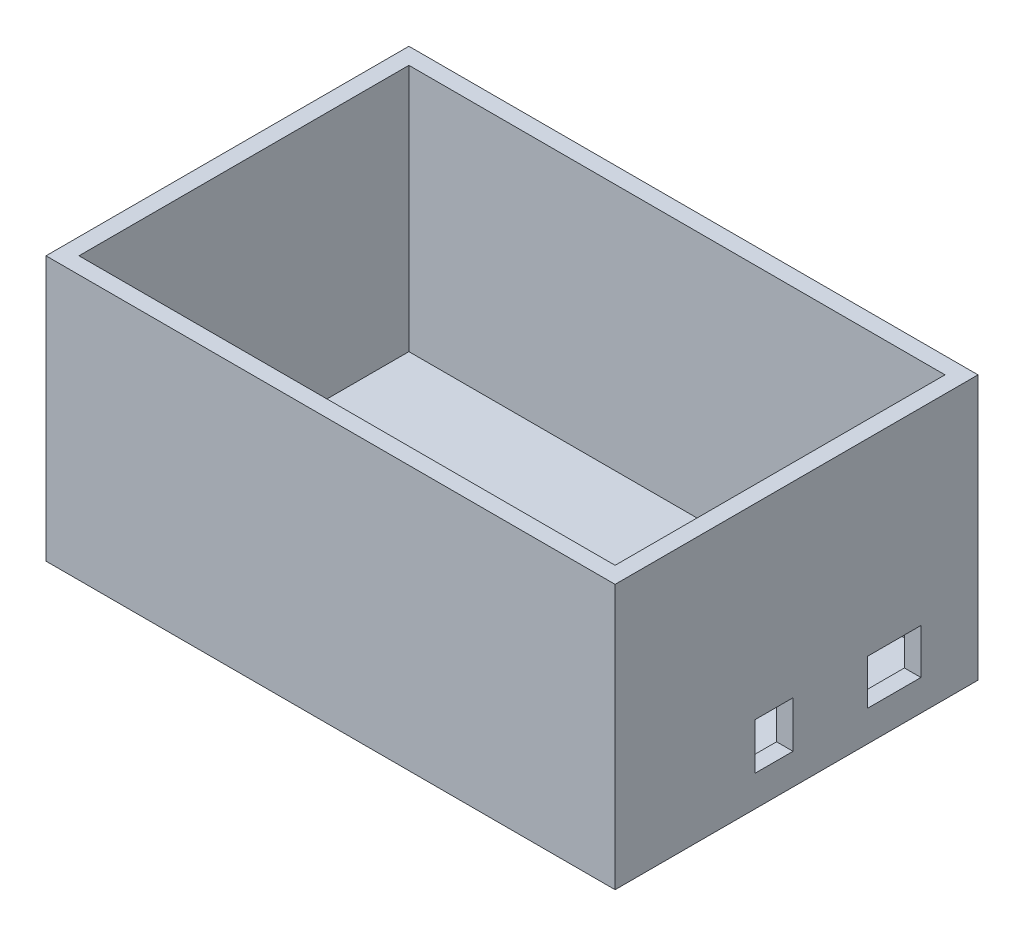
SolidWorks part; units mm, degrees
ref_plane "Front Plane" through (0, 0, 0) normal (0, 0, 1) x (1, 0, 0)
ref_plane "Top Plane" through (0, 0, 0) normal (0, 1, 0) x (1, 0, 0)
ref_plane "Right Plane" through (0, 0, 0) normal (1, 0, 0) x (0, 0, -1)
sketch "Sketch1" plane through (0, 0, 0) normal (0, 1, 0) x (1, 0, 0)
  line L1 (-39.6875, -56.885) -> (98.3125, -56.885)
  line L2 (-39.6875, -56.885) -> (-39.6875, 31.115)
  line L3 (-39.6875, 31.115) -> (98.3125, 31.115)
  line L4 (98.3125, -56.885) -> (98.3125, 31.115)
  point P0 (0, 0)
  dimension "D1" = 138
  dimension "D2" = 88
extrude "Boss-Extrude1" add sketch "Sketch1" against normal blind 24.13 and the other way blind 40
shell "Shell1" thickness 4
ref_plane "Plane3" through (0, -17.59, 0) normal (0, 1, 0) x (-1, 0, 0)
ref_plane "Plane4" through (0, -15.05, 0) normal (0, 1, 0) x (-1, 0, 0)
sketch "Sketch10" plane through (98.3125, 0, 0) normal (-1, 0, 0) x (0, 0, 1)
  line L0 (-17.145, -16.51) -> (-17.145, -5.842) construction
  line L1 (-17.272, -5.715) -> (-4.318, -5.715)
  line L2 (-17.272, -5.715) -> (-17.272, -16.637)
  line L3 (-17.272, -16.637) -> (-4.318, -16.637)
  line L4 (-4.318, -5.715) -> (-4.318, -16.637)
  line L5 (-17.145, -5.842) -> (-4.445, -5.842) construction
  line L6 (-4.445, -16.51) -> (-4.445, -5.842) construction
  line L7 (-17.145, -16.51) -> (-4.445, -16.51) construction
  dimension "D1" = 0.127
  dimension "D2" = 0.127
  dimension "D3" = 0.127
  dimension "D4" = 0.127
extrude "Cut-Extrude1" cut sketch "Sketch10" against normal up to surface (134 mm away)
sketch "Sketch12" plane through (98.3125, 0, 0) normal (-1, 0, 0) x (0, 0, 1)
  line L0 (13.86, -5.51) -> (13.86, -16.51) construction
  line L1 (13.733, -5.383) -> (22.987, -5.383)
  line L2 (13.733, -5.383) -> (13.733, -16.637)
  line L3 (13.733, -16.637) -> (22.987, -16.637)
  line L4 (22.987, -5.383) -> (22.987, -16.637)
  line L5 (22.86, -16.51) -> (22.86, -5.51) construction
  line L6 (22.86, -5.51) -> (13.86, -5.51) construction
  line L7 (13.86, -16.51) -> (22.86, -16.51) construction
  dimension "D1" = 0.127
  dimension "D2" = 0.127
  dimension "D3" = 0.127
  dimension "D4" = 0.127
extrude "Cut-Extrude2" cut sketch "Sketch12" against normal up to surface (134 mm away)
